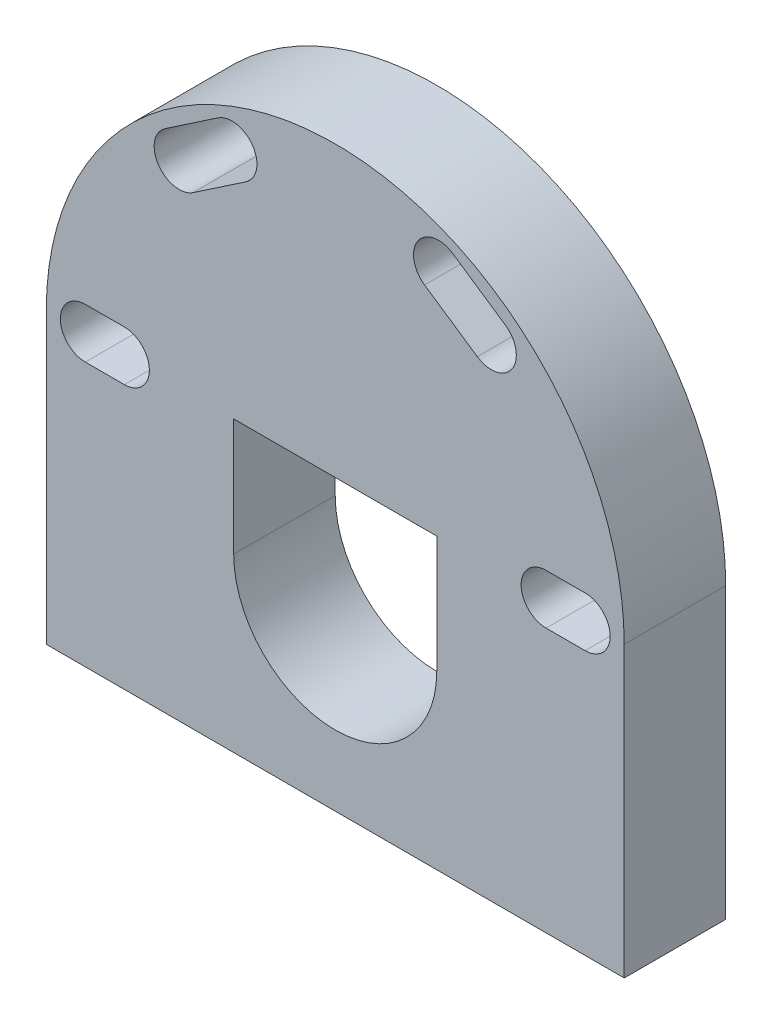
SolidWorks part; units mm, degrees
ref_plane "Ön Düzlem" through (0, 0, 0) normal (0, 0, 1) x (1, 0, 0)
ref_plane "Üst Düzlem" through (0, 0, 0) normal (0, 1, 0) x (1, 0, 0)
ref_plane "Sağ Düzlem" through (0, 0, 0) normal (1, 0, 0) x (0, 0, -1)
sketch "Çizim1" plane through (0, 0, 0) normal (0, 0, 1) x (1, 0, 0)
  circle A0 centre (0, 0) radius 18.5
  dimension "D1" = 37
extrude "Yükseklik-Ekstrüzyon1" add sketch "Çizim1" along normal blind 6.5
sketch "Çizim2" plane through (0, 0, 6.5) normal (0, 0, 1) x (1, 0, 0)
  line L0 (0, 0) -> (0, -7.5) construction
  line L1 (6.5, 0) -> (6.5, -7.5)
  line L2 (-6.5, 0) -> (-6.5, -7.5)
  line L3 (-6.5, 0) -> (6.5, 0)
  line L4 (-16, 0) -> (-13.5, 0) construction
  line L5 (-16, 1.6) -> (-13.5, 1.6)
  line L6 (-16, -1.6) -> (-13.5, -1.6)
  line L7 (16, 0) -> (13.5, 0) construction
  line L8 (16, -1.6) -> (13.5, -1.6)
  line L9 (16, 1.6) -> (13.5, 1.6)
  line L10 (6.6131, 14.8617) -> (9.9935, 12.5729) construction
  line L11 (7.5102, 16.1866) -> (10.8905, 13.8978)
  line L12 (5.7161, 13.5368) -> (9.0964, 11.2481)
  line L13 (-6.6131, 14.8617) -> (-9.9935, 12.5729) construction
  line L14 (-7.5102, 16.1866) -> (-10.8905, 13.8978)
  line L15 (-5.7161, 13.5368) -> (-9.0964, 11.2481)
  arc A0 (-16, 1.6) -> (-16, -1.6) centre (-16, 0) ccw
  arc A1 (-6.5, -7.5) -> (6.5, -7.5) centre (0, -7.5) ccw
  circle A2 centre (0, 0) radius 18.5 construction
  arc A3 (-13.5, -1.6) -> (-13.5, 1.6) centre (-13.5, 0) ccw
  arc A4 (16, -1.6) -> (16, 1.6) centre (16, 0) ccw
  arc A5 (13.5, 1.6) -> (13.5, -1.6) centre (13.5, 0) ccw
  arc A6 (7.5102, 16.1866) -> (5.7161, 13.5368) centre (6.6131, 14.8617) ccw
  arc A7 (9.0964, 11.2481) -> (10.8905, 13.8978) centre (9.9935, 12.5729) ccw
  arc A8 (-7.5102, 16.1866) -> (-5.7161, 13.5368) centre (-6.6131, 14.8617) cw
  arc A9 (-9.0964, 11.2481) -> (-10.8905, 13.8978) centre (-9.9935, 12.5729) cw
  point P3 (0, 0)
  point P6 (-14.75, 0)
  point P17 (14.75, 0)
  point P24 (8.3033, 13.7173)
  point P43 (-8.3033, 13.7173)
  dimension "D1" = 6.5
  dimension "D2" = 7.5
  dimension "D3" = 1.6
  dimension "D4" = 1.6
  dimension "D9" = 1.6
  dimension "D5" = 2.5
  dimension "D6" = 2.5
  dimension "D7" = 13.5
  dimension "D8" = 13.5
extrude "Kes-Ekstrüzyon1" cut sketch "Çizim2" against normal blind 6.5
sketch "Çizim3" plane through (0, 0, 0) normal (0, 0, -1) x (-1, 0, 0)
  line L0 (18.5, 0) -> (18.5, -18.5)
  line L1 (18.5, -18.5) -> (-18.5, -18.5)
  line L2 (-18.5, -18.5) -> (-18.5, 0)
  circle A0 centre (0, 0) radius 18.5 construction
  circle A2 centre (0, 0) radius 18.5
  circle A3 centre (0, 0) radius 18.5
  circle M22 centre (0, 0) radius 18.5
  dimension "D1" = 0
extrude "Yükseklik-Ekstrüzyon2" add sketch "Çizim3" against normal blind 6.5 contours L2 L1 M22 | L1 L0 M22
sketch "Çizim4" plane through (0, 0, 6.5) normal (0, 0, 1) x (1, 0, 0)
  line L1 (-18.5, -18.5) -> (18.5, -18.5)
  line L2 (-18.5, -18.5) -> (-18.5, -22.5)
  line L3 (-18.5, -22.5) -> (18.5, -22.5)
  line L4 (18.5, -18.5) -> (18.5, -22.5)
  dimension "D1" = 4
extrude "Yükseklik-Ekstrüzyon3" add sketch "Çizim4" along normal blind 30 and the other way up to surface (6.5 mm away) other way up to face at (-14.75, 0, 0)
sketch "Çizim5" plane through (0, -22.5, 0) normal (0, -1, 0) x (1, 0, 0)
  line L1 (-18.5, 0) -> (18.4954, 0)
  line L2 (-18.5, 0) -> (-18.5, 250)
  line L3 (-18.5, 250) -> (18.4954, 250)
  line L4 (18.4954, 0) -> (18.4954, 250)
  dimension "D1" = 250
extrude "Yükseklik-Ekstrüzyon4" add sketch "Çizim5" against normal up to surface (4 mm away) up to face at (0, -18.5, 21.5)
sketch "Çizim10" plane through (0, 0, 250) normal (0, 0, 1) x (1, 0, 0)
  line L0 (5.7161, 13.5368) -> (9.0964, 11.2481) construction
  line L1 (10.8905, 13.8978) -> (7.5102, 16.1866) construction
  line L2 (-7.5102, 16.1866) -> (-10.8905, 13.8978) construction
  line L3 (-18.5, 0) -> (-18.5, -18.5)
  line L4 (-18.5, -18.5) -> (18.5, -18.5)
  line L5 (18.5, -18.5) -> (18.5, 0)
  line L6 (-18.5, 0) -> (-18.5, -18.5)
  line L7 (-18.5, -18.5) -> (18.5, -18.5)
  line L8 (18.5, -18.5) -> (18.5, 0)
  line L9 (-9.0964, 11.2481) -> (-5.7161, 13.5368) construction
  line L10 (-13.5, 1.6) -> (-16, 1.6) construction
  line L11 (-16, -1.6) -> (-13.5, -1.6) construction
  line L12 (6.5, -7.5) -> (6.5, 0) construction
  line L13 (13.5, -1.6) -> (16, -1.6) construction
  line L14 (16, 1.6) -> (13.5, 1.6) construction
  line L15 (6.5, 0) -> (-6.5, 0) construction
  line L16 (-6.5, 0) -> (-6.5, -7.5) construction
  line L17 (5.7161, 13.5368) -> (9.0964, 11.2481)
  line L18 (10.8905, 13.8978) -> (7.5102, 16.1866)
  line L19 (-7.5102, 16.1866) -> (-10.8905, 13.8978)
  line L20 (-9.0964, 11.2481) -> (-5.7161, 13.5368)
  line L21 (-13.5, 1.6) -> (-16, 1.6)
  line L22 (-16, -1.6) -> (-13.5, -1.6)
  line L23 (6.5, -7.5) -> (6.5, 0)
  line L24 (13.5, -1.6) -> (16, -1.6)
  line L25 (16, 1.6) -> (13.5, 1.6)
  line L26 (6.5, 0) -> (-6.5, 0)
  line L27 (-6.5, 0) -> (-6.5, -7.5)
  arc A0 (9.0964, 11.2481) -> (10.8905, 13.8978) centre (9.9935, 12.5729) ccw construction
  arc A1 (18.5, 0) -> (-18.5, 0) centre (0, 0) ccw
  arc A2 (18.5, 0) -> (-18.5, 0) centre (0, 0) ccw
  arc A3 (7.5102, 16.1866) -> (5.7161, 13.5368) centre (6.6131, 14.8617) ccw construction
  arc A4 (-5.7161, 13.5368) -> (-7.5102, 16.1866) centre (-6.6131, 14.8617) ccw construction
  arc A5 (-10.8905, 13.8978) -> (-9.0964, 11.2481) centre (-9.9935, 12.5729) ccw construction
  arc A6 (-13.5, -1.6) -> (-13.5, 1.6) centre (-13.5, 0) ccw construction
  arc A7 (-16, 1.6) -> (-16, -1.6) centre (-16, 0) ccw construction
  arc A8 (-6.5, -7.5) -> (6.5, -7.5) centre (0, -7.5) ccw construction
  arc A9 (16, -1.6) -> (16, 1.6) centre (16, 0) ccw construction
  arc A10 (13.5, 1.6) -> (13.5, -1.6) centre (13.5, 0) ccw construction
  arc A11 (9.0964, 11.2481) -> (10.8905, 13.8978) centre (9.9935, 12.5729) ccw
  arc A12 (7.5102, 16.1866) -> (5.7161, 13.5368) centre (6.6131, 14.8617) ccw
  arc A13 (-5.7161, 13.5368) -> (-7.5102, 16.1866) centre (-6.6131, 14.8617) ccw
  arc A14 (-10.8905, 13.8978) -> (-9.0964, 11.2481) centre (-9.9935, 12.5729) ccw
  arc A15 (-13.5, -1.6) -> (-13.5, 1.6) centre (-13.5, 0) ccw
  arc A16 (-16, 1.6) -> (-16, -1.6) centre (-16, 0) ccw
  arc A17 (-6.5, -7.5) -> (6.5, -7.5) centre (0, -7.5) ccw
  arc A18 (16, -1.6) -> (16, 1.6) centre (16, 0) ccw
  arc A19 (13.5, 1.6) -> (13.5, -1.6) centre (13.5, 0) ccw
  dimension "D1" = 0
extrude "Yükseklik-Ekstrüzyon6" add sketch "Çizim10" against normal blind 6.5
sketch "Çizim12" plane through (0, -18.5, 0) normal (0, 1, 0) x (1, 0, 0)
  line L0 (-18.5, 0) -> (-18.5, -250)
  arc A0 (-18.5, 0) -> (-18.5, -250) centre (-11.2986, -125) ccw
extrude "Yükseklik-Ekstrüzyon7" add sketch "Çizim12" against normal up to surface (4 mm away) up to face at (6.1651, -22.5, 95.5)
sketch "Çizim14" plane through (0, -22.5, 0) normal (0, -1, 0) x (1, 0, 0)
  line L5 (18.5, 36.5) -> (18.4954, 36.5)
  line L6 (18.4954, 36.5) -> (18.4954, 250)
  line L7 (18.4954, 250) -> (-18.5, 250)
  line L8 (-18.5, 0) -> (18.5, 0)
  line L9 (18.5, 0) -> (18.5, 36.5)
  line L10 (18.5, 36.5) -> (18.4954, 36.5)
  line L11 (18.4954, 36.5) -> (18.4954, 250)
  line L12 (18.4954, 250) -> (-18.5, 250)
  line L13 (-18.5, 0) -> (18.5, 0)
  line L14 (18.5, 0) -> (18.5, 36.5)
  arc A1 (-18.5, 250) -> (-18.5, 0) centre (-11.2986, 125) ccw
  arc A2 (-18.5, 250) -> (-18.5, 0) centre (-11.2986, 125) ccw
  dimension "D1" = 0
extrude "Yükseklik-Ekstrüzyon8" add sketch "Çizim14" along normal blind 6
sketch "Çizim15" plane through (0, -18.5, 0) normal (0, 1, 0) x (1, 0, 0)
  line L0 (18.5, 0) -> (-18.5, 0) construction
  line L1 (-18.5, 0) -> (-189.1215, 0)
  line L2 (-18.5, 0) -> (-18.5, -260.4008)
  line L3 (-18.5, -260.4008) -> (-189.1215, -260.4008)
  line L4 (-189.1215, 0) -> (-189.1215, -260.4008)
extrude "Kes-Ekstrüzyon2" cut sketch "Çizim15" against normal blind 75.7521
sketch "Çizim16" plane through (0, -28.5, 0) normal (0, -1, 0) x (1, 0, 0)
  line L6 (-18.5, 250) -> (-18.5, 0)
  line L7 (-18.5, 0) -> (18.5, 0)
  line L8 (18.5, 0) -> (18.5, 36.5)
  line L9 (18.5, 36.5) -> (18.4954, 36.5)
  line L10 (18.4954, 36.5) -> (18.4954, 250)
  line L11 (18.4954, 250) -> (-18.5, 250)
  line L12 (-18.5, 250) -> (-18.5, 0)
  line L13 (-18.5, 0) -> (18.5, 0)
  line L14 (18.5, 0) -> (18.5, 36.5)
  line L15 (18.5, 36.5) -> (18.4954, 36.5)
  line L16 (18.4954, 36.5) -> (18.4954, 250)
  line L17 (18.4954, 250) -> (-18.5, 250)
  dimension "D1" = 0
extrude "Kes-Ekstrüzyon3" cut sketch "Çizim16" against normal blind 8
sketch "Çizim17" plane through (0, -18.5, 0) normal (0, 1, 0) x (1, 0, 0)
  line L1 (-18.5, -243.5) -> (67.0336, -243.5)
  line L2 (-18.5, -243.5) -> (-18.5, 76.9771)
  line L3 (-18.5, 76.9771) -> (67.0336, 76.9771)
  line L4 (67.0336, -243.5) -> (67.0336, 76.9771)
extrude "Kes-Ekstrüzyon4" cut sketch "Çizim17" against normal blind 8
sketch "Çizim18" plane through (0, 0, 243.5) normal (0, 0, -1) x (-1, 0, 0)
  line L5 (-18.5, 0) -> (-18.5, -18.5)
  line L6 (-18.5, -18.5) -> (-18.4954, -18.5)
  line L7 (-18.4954, -18.5) -> (-18.4954, -20.5)
  line L8 (-18.4954, -20.5) -> (18.5, -20.5)
  line L9 (18.5, -20.5) -> (18.5, 0)
  line L10 (-18.5, 0) -> (-18.5, -18.5)
  line L11 (-18.5, -18.5) -> (-18.4954, -18.5)
  line L12 (-18.4954, -18.5) -> (-18.4954, -20.5)
  line L13 (-18.4954, -20.5) -> (18.5, -20.5)
  line L14 (18.5, -20.5) -> (18.5, 0)
  arc A1 (18.5, 0) -> (-18.5, 0) centre (0, 0) ccw
  arc A2 (18.5, 0) -> (-18.5, 0) centre (0, 0) ccw
  dimension "D1" = 0
extrude "Kes-Ekstrüzyon5" cut sketch "Çizim18" against normal blind 8
